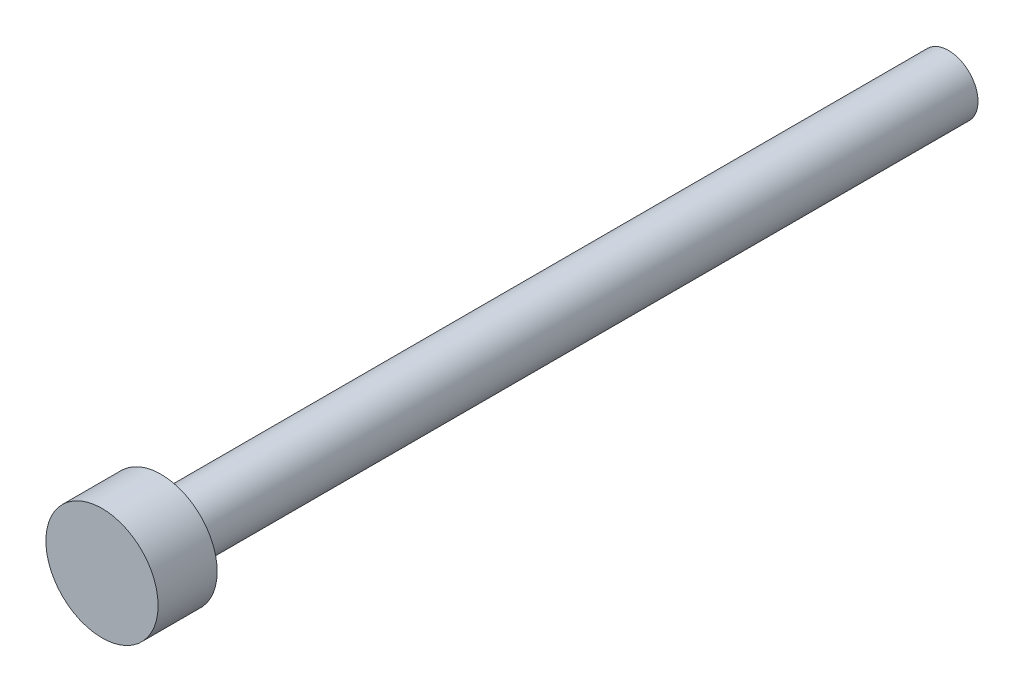
SolidWorks part; units mm, degrees
ref_plane "Front Plane" through (0, 0, 0) normal (0, 0, 1) x (1, 0, 0)
ref_plane "Top Plane" through (0, 0, 0) normal (0, 1, 0) x (1, 0, 0)
ref_plane "Right Plane" through (0, 0, 0) normal (1, 0, 0) x (0, 0, -1)
sketch "Sketch1" plane through (0, 0, 0) normal (0, 0, 1) x (1, 0, 0)
  circle A0 centre (0, 0) radius 1.5
  dimension "D1" = 3
extrude "Boss-Extrude1" add sketch "Sketch1" along normal blind 40
sketch "Sketch2" plane through (0, 0, 40) normal (0, 0, 1) x (1, 0, 0)
  circle A0 centre (0, 0) radius 2.85
  dimension "D1" = 5.7
extrude "Boss-Extrude2" add sketch "Sketch2" along normal blind 3
